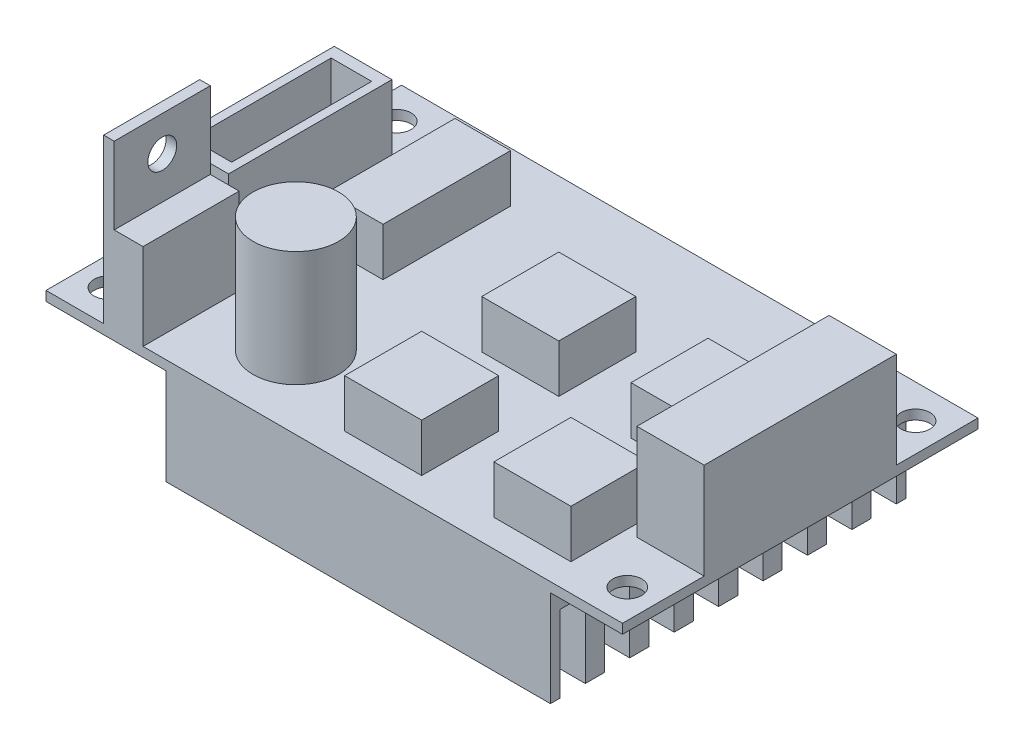
SolidWorks part; units mm, degrees
material "ABS"
ref_plane "前视基准面" through (0, 0, 0) normal (0, 0, 1) x (1, 0, 0)
ref_plane "上视基准面" through (0, 0, 0) normal (0, 1, 0) x (1, 0, 0)
ref_plane "右视基准面" through (0, 0, 0) normal (1, 0, 0) x (0, 0, -1)
sketch "草图1" plane through (0, 0, 0) normal (0, 1, 0) x (1, 0, 0)
  line L0 (-30, 0) -> (30, 0) construction
  line L1 (-30, 18.5) -> (30, 18.5)
  line L2 (-30, 18.5) -> (-30, -18.5)
  line L3 (-30, -18.5) -> (30, -18.5)
  line L4 (30, 18.5) -> (30, -18.5)
  line L5 (-30, 18.5) -> (30, -18.5) construction
  line L6 (-30, -18.5) -> (30, 18.5) construction
  line L7 (0, 18.5) -> (0, -18.5) construction
  circle A0 centre (27, 15) radius 1.5
  circle A1 centre (27, -15) radius 1.5
  circle A2 centre (-27, -15) radius 1.5
  circle A3 centre (-27, 15) radius 1.5
  point P0 (0, 0)
  dimension "D3" = 15
  dimension "D4" = 27
  dimension "D1" = 37
  dimension "D2" = 60
extrude "凸台-拉伸1" add sketch "草图1" along normal blind 1
sketch "草图2" plane through (0, 1, 0) normal (0, 1, 0) x (1, 0, 0)
  line L0 (-30, 0) -> (30, 0) construction
  line L1 (-30, 18.5) -> (-30, -18.5) construction
  line L2 (30, -18.5) -> (30, 18.5) construction
  line L5 (23, 10) -> (23, -10)
  line L8 (23, 10) -> (41, 10)
  line L9 (41, 10) -> (41, -10)
  line L10 (41, -10) -> (23, -10)
extrude "凸台-拉伸2" add sketch "草图2" along normal blind 10
sketch "草图3" plane through (0, 11, 0) normal (0, 1, 0) x (1, 0, 0)
  line L0 (38.5621, 10) -> (38.5621, 5) construction
  line L1 (41, 10) -> (23, 10) construction
  line L2 (38.5621, 5) -> (38.5621, 0) construction
  line L3 (38.5621, 0) -> (41, 0) construction
  line L4 (41, -10) -> (41, 10) construction
  line L6 (38.5621, 5) -> (41, 5) construction
  circle A0 centre (38.5621, 7.5) radius 1
  circle A1 centre (38.5621, 2.5) radius 1
  circle A2 centre (38.5621, -7.5) radius 1
  circle A3 centre (38.5621, -2.5) radius 1
extrude "切除-拉伸1" cut sketch "草图3" against normal blind 1
sketch "草图4" plane through (41, 0, 0) normal (1, 0, 0) x (0, 0, -1)
  line L0 (-5, 3.7306) -> (-10, 3.7306) construction
  line L3 (0, 3.7306) -> (0, 11) construction
  line L4 (-10, 11) -> (10, 11) construction
  line L6 (-5, 3.7306) -> (-5, 11) construction
  line L7 (-10, 11) -> (-10, 1) construction
  line L8 (-5, 3.7306) -> (0, 3.7306) construction
  line L9 (-1.5553, 1.8162) -> (-3.4447, 1.8162)
  line L10 (-8.4447, 5.645) -> (-6.5553, 5.645)
  line L11 (-8.4447, 5.645) -> (-8.4447, 1.8162)
  line L12 (-8.4447, 1.8162) -> (-6.5553, 1.8162)
  line L13 (-6.5553, 5.645) -> (-6.5553, 1.8162)
  line L14 (-8.4447, 5.645) -> (-6.5553, 1.8162) construction
  line L15 (-8.4447, 1.8162) -> (-6.5553, 5.645) construction
  line L16 (-3.4447, 5.645) -> (-3.4447, 1.8162)
  line L17 (-1.5553, 5.645) -> (-3.4447, 5.645)
  line L18 (-1.5553, 5.645) -> (-1.5553, 1.8162)
  line L19 (-1.5553, 1.8162) -> (-3.4447, 5.645) construction
  line L20 (-1.5553, 5.645) -> (-3.4447, 1.8162) construction
  line L21 (1.5553, 5.645) -> (3.4447, 1.8162) construction
  line L22 (1.5553, 1.8162) -> (3.4447, 5.645) construction
  line L23 (8.4447, 1.8162) -> (6.5553, 5.645) construction
  line L24 (8.4447, 5.645) -> (6.5553, 1.8162) construction
  line L25 (1.5553, 5.645) -> (1.5553, 1.8162)
  line L26 (1.5553, 5.645) -> (3.4447, 5.645)
  line L27 (3.4447, 5.645) -> (3.4447, 1.8162)
  line L28 (6.5553, 5.645) -> (6.5553, 1.8162)
  line L29 (8.4447, 1.8162) -> (6.5553, 1.8162)
  line L30 (8.4447, 5.645) -> (8.4447, 1.8162)
  line L31 (8.4447, 5.645) -> (6.5553, 5.645)
  line L32 (1.5553, 1.8162) -> (3.4447, 1.8162)
  point P1 (-7.5, 3.7306)
  point P18 (-2.5, 3.7306)
  point P27 (2.5, 3.7306)
  point P28 (7.5, 3.7306)
extrude "切除-拉伸2" cut sketch "草图4" against normal blind 5
sketch "草图5" plane through (0, 1, 0) normal (0, 1, 0) x (1, 0, 0)
  line L0 (-30, 11.5) -> (-24, 11.5)
  line L1 (-30, 18.5) -> (-30, -18.5) construction
  line L2 (-24, 11.5) -> (-24, -5.5)
  line L3 (-24, -5.5) -> (-30, -5.5)
  line L4 (-30, -5.5) -> (-30, 11.5)
  line L5 (30, 18.5) -> (-30, 18.5) construction
  dimension "D1" = 7
  dimension "D2" = 17
extrude "凸台-拉伸3" add sketch "草图5" along normal blind 7
sketch "草图6" plane through (0, 8, 0) normal (0, 1, 0) x (1, 0, 0)
  line L0 (-27, 11.5) -> (-27, -5.5) construction
  line L1 (-24, 11.5) -> (-30, 11.5) construction
  line L2 (-30, -5.5) -> (-24, -5.5) construction
  line L4 (-29.1096, 10.2858) -> (-24.8904, 10.2858)
  line L5 (-29.1096, 10.2858) -> (-29.1096, -4.2858)
  line L6 (-29.1096, -4.2858) -> (-24.8904, -4.2858)
  line L7 (-24.8904, 10.2858) -> (-24.8904, -4.2858)
  line L8 (-29.1096, 10.2858) -> (-24.8904, -4.2858) construction
  line L9 (-29.1096, -4.2858) -> (-24.8904, 10.2858) construction
  point P6 (-27, 3)
extrude "切除-拉伸3" cut sketch "草图6" against normal blind 7
sketch "草图7" plane through (0, 1, 0) normal (0, 1, 0) x (1, 0, 0)
  line L0 (-24, -18.5) -> (-22.9005, -18.5)
  line L1 (-30, -18.5) -> (30, -18.5) construction
  line L3 (-22.9005, -8.5) -> (-24, -8.5)
  line L4 (-24, -8.5) -> (-24, -18.5)
  line L5 (-22.9005, -8.5) -> (-22.9005, -18.5)
extrude "凸台-拉伸4" add sketch "草图7" along normal blind 17
sketch "草图8" plane through (0, 1, 0) normal (0, 1, 0) x (1, 0, 0)
  line L0 (-22.9005, -8.5) -> (-19.9005, -8.5)
  line L1 (-22.9005, -8.5) -> (-24, -8.5) construction
  line L2 (-19.9005, -8.5) -> (-19.9005, -18.5)
  line L3 (-22.9005, -18.5) -> (30, -18.5) construction
  line L4 (-19.9005, -18.5) -> (-22.9005, -18.5)
  line L5 (-22.9005, -18.5) -> (-22.9005, -8.5)
extrude "凸台-拉伸5" add sketch "草图8" along normal blind 9
sketch "草图9" plane through (-22.9005, 0, 0) normal (1, 0, 0) x (0, 0, -1)
  circle A0 centre (-13.5, 14.3661) radius 1.5
extrude "切除-拉伸4" cut sketch "草图9" against normal blind 9
sketch "草图10" plane through (0, 1, 0) normal (0, 1, 0) x (1, 0, 0)
  line L0 (0, 18.5) -> (0, -18.5) construction
  line L1 (30, 18.5) -> (-30, 18.5) construction
  line L2 (-19.9005, -18.5) -> (30, -18.5) construction
  line L3 (0, 0) -> (51.8092, 0) construction
  line L5 (-1.7734, 6.6424) -> (6.2416, 6.6424)
  line L6 (-1.7734, 6.6424) -> (-1.7734, -1.3727)
  line L7 (-1.7734, -1.3727) -> (6.2416, -1.3727)
  line L8 (6.2416, 6.6424) -> (6.2416, -1.3727)
  line L9 (-1.7734, 6.6424) -> (6.2416, -1.3727) construction
  line L10 (-1.7734, -1.3727) -> (6.2416, 6.6424) construction
  line L11 (-19.2131, 13.2847) -> (-13.4244, 13.2847)
  line L12 (21.7734, -1.3727) -> (13.7584, 6.6424) construction
  line L13 (21.7734, 6.6424) -> (13.7584, -1.3727) construction
  line L14 (13.7584, 6.6424) -> (13.7584, -1.3727)
  line L15 (21.7734, -1.3727) -> (13.7584, -1.3727)
  line L16 (21.7734, 6.6424) -> (21.7734, -1.3727)
  line L17 (21.7734, 6.6424) -> (13.7584, 6.6424)
  line L18 (21.7734, -15.6424) -> (13.7584, -7.6273) construction
  line L19 (21.7734, -7.6273) -> (13.7584, -15.6424) construction
  line L20 (-1.7734, -7.6273) -> (6.2416, -15.6424) construction
  line L21 (-1.7734, -15.6424) -> (6.2416, -7.6273) construction
  line L22 (21.7734, -15.6424) -> (13.7584, -15.6424)
  line L23 (21.7734, -15.6424) -> (21.7734, -7.6273)
  line L24 (21.7734, -7.6273) -> (13.7584, -7.6273)
  line L25 (13.7584, -15.6424) -> (13.7584, -7.6273)
  line L26 (6.2416, -15.6424) -> (6.2416, -7.6273)
  line L27 (-1.7734, -7.6273) -> (6.2416, -7.6273)
  line L28 (-1.7734, -15.6424) -> (-1.7734, -7.6273)
  line L29 (-1.7734, -15.6424) -> (6.2416, -15.6424)
  line L31 (-19.2131, 13.2847) -> (-19.2131, 0)
  line L32 (-19.2131, 0) -> (-13.4244, 0)
  line L33 (-13.4244, 13.2847) -> (-13.4244, 0)
  line L34 (-19.2131, 13.2847) -> (-13.4244, 0) construction
  line L35 (-19.2131, 0) -> (-13.4244, 13.2847) construction
  point P9 (2.2341, 2.6348)
  point P14 (-16.3187, 6.6424)
  point P22 (17.7659, 2.6348)
  point P31 (17.7659, -11.6348)
  point P32 (2.2341, -11.6348)
extrude "凸台-拉伸7" add sketch "草图10" along normal blind 5
sketch "草图11" plane through (0, 1, 0) normal (0, 1, 0) x (1, 0, 0)
  circle A0 centre (-11.6433, -10.8537) radius 4.4528
extrude "凸台-拉伸8" add sketch "草图11" along normal blind 12
sketch "草图12" plane through (0, 0, 0) normal (0, -1, 0) x (1, 0, 0)
  line L0 (22.5, 18.5) -> (22.5, -18.5)
  line L1 (-30, 18.5) -> (30, 18.5) construction
  line L2 (30, -18.5) -> (-30, -18.5) construction
  line L3 (22.5, -18.5) -> (-17.5, -18.5)
  line L4 (-17.5, -18.5) -> (-17.5, 18.5)
  line L5 (-17.5, 18.5) -> (22.5, 18.5)
  line L6 (30, 18.5) -> (30, -18.5) construction
  dimension "D1" = 7.5
  dimension "D2" = 40
extrude "凸台-拉伸9" add sketch "草图12" along normal blind 10
sketch "草图13" plane through (-17.5, 0, 0) normal (-1, 0, 0) x (0, 0, 1)
  line L0 (0, -10) -> (0, 0) construction
  line L1 (18.5, -10) -> (-18.5, -10) construction
  line L2 (-9.25, -5) -> (-18.5, -5) construction
  line L3 (-17.5, -10) -> (-14.87, -10)
  line L4 (-9.25, -5) -> (-9.25, -10) construction
  line L5 (-18.5, -10) -> (-18.5, 0) construction
  line L6 (-13.875, -5) -> (-13.875, -10) construction
  line L7 (-17.5, -10) -> (-17.5, -2.0043)
  line L8 (-17.5, -2.0043) -> (-14.87, -2.0043)
  line L9 (-14.87, -2.0043) -> (-14.87, -10)
  line L10 (-12.88, -2.0043) -> (-12.88, -10)
  line L11 (-10.25, -2.0043) -> (-12.88, -2.0043)
  line L12 (-10.25, -10) -> (-10.25, -2.0043)
  line L13 (-10.25, -10) -> (-12.88, -10)
  line L14 (-8.25, -10) -> (-5.62, -10)
  line L15 (-8.25, -10) -> (-8.25, -2.0043)
  line L16 (-8.25, -2.0043) -> (-5.62, -2.0043)
  line L17 (-5.62, -2.0043) -> (-5.62, -10)
  line L18 (-3.63, -2.0043) -> (-3.63, -10)
  line L19 (-1, -2.0043) -> (-3.63, -2.0043)
  line L20 (-1, -10) -> (-1, -2.0043)
  line L21 (-1, -10) -> (-3.63, -10)
  line L22 (1, -10) -> (3.63, -10)
  line L23 (1, -10) -> (1, -2.0043)
  line L24 (1, -2.0043) -> (3.63, -2.0043)
  line L25 (3.63, -2.0043) -> (3.63, -10)
  line L26 (5.62, -2.0043) -> (5.62, -10)
  line L27 (8.25, -2.0043) -> (5.62, -2.0043)
  line L28 (8.25, -10) -> (8.25, -2.0043)
  line L29 (8.25, -10) -> (5.62, -10)
  line L30 (10.25, -10) -> (12.88, -10)
  line L31 (10.25, -10) -> (10.25, -2.0043)
  line L32 (10.25, -2.0043) -> (12.88, -2.0043)
  line L33 (12.88, -2.0043) -> (12.88, -10)
  line L34 (14.87, -2.0043) -> (14.87, -10)
  line L35 (17.5, -2.0043) -> (14.87, -2.0043)
  line L36 (17.5, -10) -> (17.5, -2.0043)
  line L37 (17.5, -10) -> (14.87, -10)
  dimension "D1" = 1
  dimension "D2" = 2.63
extrude "切除-拉伸5" cut sketch "草图13" against normal through all
sketch "草图14" plane through (0, 0, 0) normal (0, -1, 0) x (1, 0, 0)
  line L1 (30, 10) -> (41, 10)
  line L2 (30, 10) -> (30, -10)
  line L3 (30, -10) -> (41, -10)
  line L4 (41, 10) -> (41, -10)
extrude "切除-拉伸6" cut sketch "草图14" against normal through all
